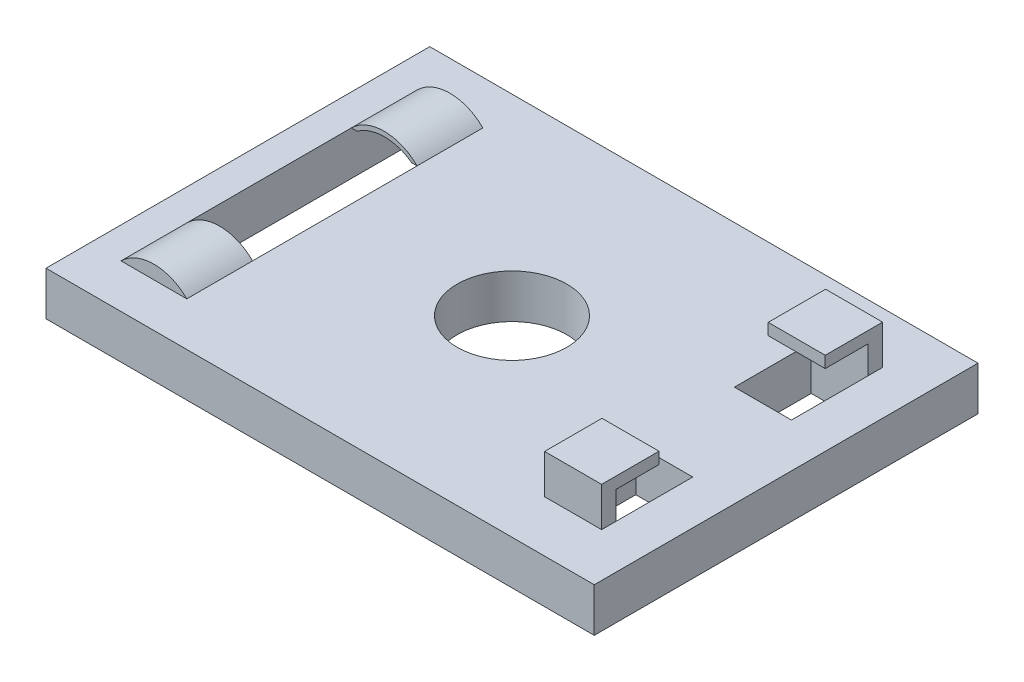
SolidWorks part; units mm, degrees
ref_plane "前视基准面" through (0, 0, 0) normal (0, 0, 1) x (1, 0, 0)
ref_plane "上视基准面" through (0, 0, 0) normal (0, 1, 0) x (1, 0, 0)
ref_plane "右视基准面" through (0, 0, 0) normal (1, 0, 0) x (0, 0, -1)
sketch "草图1" plane through (0, 0, 0) normal (0, 1, 0) x (1, 0, 0)
  line L1 (-12.5, -8.75) -> (12.5, -8.75)
  line L2 (-12.5, -8.75) -> (-12.5, 8.75)
  line L3 (-12.5, 8.75) -> (12.5, 8.75)
  line L4 (12.5, -8.75) -> (12.5, 8.75)
  line L5 (0, 8.75) -> (0, -8.75) construction
  line L6 (-12.5, 0) -> (12.5, 0) construction
  point P0 (0, 0)
  dimension "D1" = 25
  dimension "D2" = 17.5
extrude "凸台-拉伸1" add sketch "草图1" along normal blind 2
sketch "草图2" plane through (0, 2, 0) normal (0, 1, 0) x (1, 0, 0)
  circle A0 centre (0, 0) radius 2.5
extrude "切除-拉伸1" cut sketch "草图2" against normal blind 2
sketch "草图3" plane through (0, 2, 0) normal (0, 1, 0) x (1, 0, 0)
  line L0 (15.2677, 0) -> (-16.0819, 0) construction
  line L1 (12.5, 8.75) -> (-12.5, 8.75) construction
  line L2 (10.4935, 5.75) -> (7.8935, 5.75)
  line L3 (10.4935, 5.75) -> (10.4935, 2.25)
  line L4 (10.4935, 2.25) -> (7.8935, 2.25)
  line L5 (7.8935, 5.75) -> (7.8935, 2.25)
  line L6 (10.4935, -5.75) -> (7.8935, -5.75)
  line L7 (7.8935, -5.75) -> (7.8935, -2.25)
  line L8 (10.4935, -2.25) -> (7.8935, -2.25)
  line L9 (10.4935, -5.75) -> (10.4935, -2.25)
  dimension "D1" = 3.5
  dimension "D2" = 2.6
  dimension "D3" = 3
extrude "切除-拉伸2" cut sketch "草图3" against normal blind 2
sketch "草图4" plane through (0, 2, 0) normal (0, 1, 0) x (1, 0, 0)
  line L0 (12.5, 8.75) -> (-12.5, 8.75) construction
  line L1 (-11.0788, 6.75) -> (-8.0788, 6.75)
  line L2 (-11.0788, 6.75) -> (-11.0788, -6.75)
  line L3 (-11.0788, -6.75) -> (-8.0788, -6.75)
  line L4 (-8.0788, 6.75) -> (-8.0788, -6.75)
  line L7 (-12.5, -8.75) -> (12.5, -8.75) construction
  dimension "D1" = 3
  dimension "D2" = 2
  dimension "D3" = 2
extrude "切除-拉伸3" cut sketch "草图4" against normal blind 2
ref_plane "基准面1" through (0, 0, 0) normal (0, 0, 1) x (1, 0, 0)
ref_plane "基准面2" through (0, 0, 0) normal (1, 0, 0) x (0, 0, -1)
sketch "草图5" plane through (10.4935, 0, 0) normal (-1, 0, 0) x (0, 0, 1)
  line L0 (-5.75, 2) -> (-6.4064, 2)
  line L1 (-6.4064, 2) -> (-6.4064, 3.7892)
  line L2 (-6.4064, 3.7892) -> (-3.7895, 3.7892)
  line L3 (-3.7895, 3.7892) -> (-3.7895, 3.2631)
  line L4 (-3.7895, 3.2631) -> (-5.75, 3.2631)
  line L5 (-5.75, 3.2631) -> (-5.75, 2)
extrude "凸台-拉伸2" add sketch "草图5" along normal up to surface (2.6 mm away) up to face at (7.8935, 1, -4)
mirror "镜向1" about plane through (0, 0, 0) normal (0, 0, 1) of "凸台-拉伸2"
sketch "草图6" plane through (0, 0, -6.75) normal (0, 0, 1) x (1, 0, 0)
  line L0 (-11.0788, 2) -> (-8.0788, 2)
  arc A0 (-11.0788, 2) -> (-8.0788, 2) centre (-9.5788, 0.5) cw
extrude "凸台-拉伸3" add sketch "草图6" along normal blind 3 separate body
sketch "草图7" plane through (0, 0, 6.75) normal (0, 0, -1) x (-1, 0, 0)
  line L1 (8.0788, 2) -> (11.0788, 2)
  line L2 (8.0788, 2) -> (11.0788, 2)
  arc A1 (11.0788, 2) -> (8.0788, 2) centre (9.5788, 0.5) ccw
  arc A2 (11.0788, 2) -> (8.0788, 2) centre (9.5788, 0.5) ccw
  dimension "D1" = 0
extrude "凸台-拉伸4" add sketch "草图7" along normal blind 3 separate body
sketch "草图8" plane through (0, 0, 0) normal (0, 0, 1) x (1, 0, 0)
  line L0 (-11.0788, 2) -> (-8.0788, 2) construction
  line L1 (-11.0788, 2) -> (-8.0788, 2)
  circle A1 centre (-9.5697, 0.2869) radius 2.12
  point P4 (-9.5697, 0.2869)
extrude "切除-拉伸5" cut sketch "草图8" against normal mid plane 13 contours L1 A1
